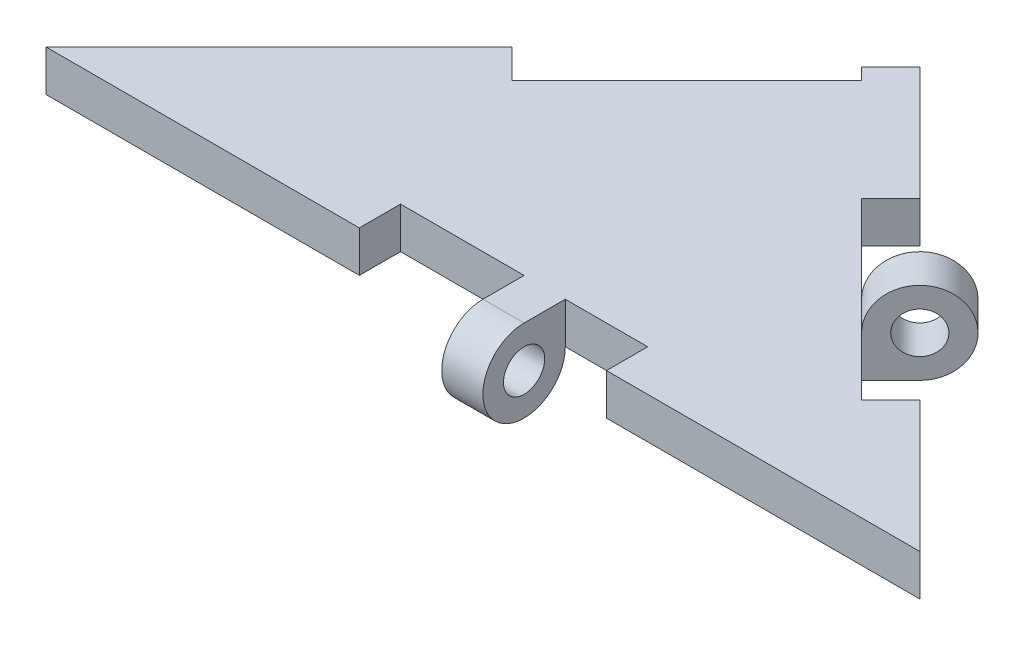
SolidWorks part; units mm, degrees
material "PET"
ref_plane "Front Plane" through (0, 0, 0) normal (0, 0, 1) x (1, 0, 0)
ref_plane "Top Plane" through (0, 0, 0) normal (0, 1, 0) x (1, 0, 0)
ref_plane "Right Plane" through (0, 0, 0) normal (1, 0, 0) x (0, 0, -1)
other "Center of Mass"
sketch "Sketch1" plane through (0, 0, 0) normal (0, 1, 0) x (1, 0, 0)
  line L0 (-53.033, 0) -> (53.033, 0)
  line L1 (-53.033, 0) -> (0, 53.033)
  line L2 (0, 53.033) -> (53.033, 0)
  dimension "D1" = 75
extrude "Boss-Extrude1" add sketch "Sketch1" along normal blind 5
sketch "Sketch2" plane through (0, 5, 0) normal (0, 1, 0) x (1, 0, 0)
  line L0 (-15, 0) -> (15, 0)
  line L1 (-15, 0) -> (-15, 5)
  line L2 (15, 0) -> (15, 5)
  line L3 (-15, 5) -> (15, 5)
  line L4 (-53.033, 0) -> (53.033, 0) construction
  line L5 (0, 0) -> (0, 8.7982) construction
  line L6 (-3.5355, 49.4975) -> (-24.7487, 28.2843)
  line L7 (-3.5355, 49.4975) -> (0, 45.9619)
  line L8 (-24.7487, 28.2843) -> (-21.2132, 24.7487)
  line L9 (0, 45.9619) -> (-21.2132, 24.7487)
  line L10 (0, 53.033) -> (-53.033, 0) construction
  line L12 (53.033, 0) -> (0, 53.033) construction
  dimension "D1" = 5
  dimension "D2" = 30
  dimension "D3" = 5
  dimension "D4" = 30
  dimension "D5" = 5
extrude "Cut-Extrude1" cut sketch "Sketch2" against normal blind 5
sketch "Sketch3" plane through (0, 0, 0) normal (0, -1, 0) x (1, 0, 0)
  line L0 (15.9099, -37.1231) -> (37.1231, -15.9099)
  line L1 (15.9099, -37.1231) -> (12.3744, -33.5876)
  line L2 (37.1231, -15.9099) -> (33.5876, -12.3744)
  line L3 (12.3744, -33.5876) -> (33.5876, -12.3744)
  line L4 (53.033, 0) -> (0, -53.033) construction
  line L5 (26.5165, -26.5165) -> (15.28, -15.28) construction
  dimension "D1" = 5
  dimension "D2" = 30
extrude "Cut-Extrude2" cut sketch "Sketch3" against normal blind 5
sketch "Sketch5" plane through (15, 0, 0) normal (-1, 0, 0) x (0, 0, 1)
  circle A0 centre (0, 0) radius 5
  circle A1 centre (0, 0) radius 2.5
  dimension "D1" = 5
extrude "Boss-Extrude2" add sketch "Sketch5" along normal blind 5 from offset 10
sketch "Sketch6" plane through (10.6066, 0, 10.6066) normal (-0.7071, 0, -0.7071) x (-0.7071, 0, 0.7071)
  circle A0 centre (-37.5, 5) radius 5
  circle A1 centre (-37.5, 5) radius 2.5
  dimension "D1" = 5
extrude "Boss-Extrude3" add sketch "Sketch6" along normal blind 5 from offset 10
sketch "Sketch7" plane through (0, 5, 0) normal (0, 1, 0) x (1, 0, 0)
  line L0 (-20.1159, 32.9171) -> (0, 53.033)
  line L1 (-20.1159, 32.9171) -> (-17.9946, 30.7958)
  line L2 (0, 53.033) -> (2.1213, 50.9117)
  line L3 (-17.9946, 30.7958) -> (2.1213, 50.9117)
  dimension "D1" = 3
extrude "Cut-Extrude3" cut sketch "Sketch7" against normal blind 10
chamfer "Chamfer1" [suppressed] distance 2 angle 45
other "Center of Mass Reference Point1"
